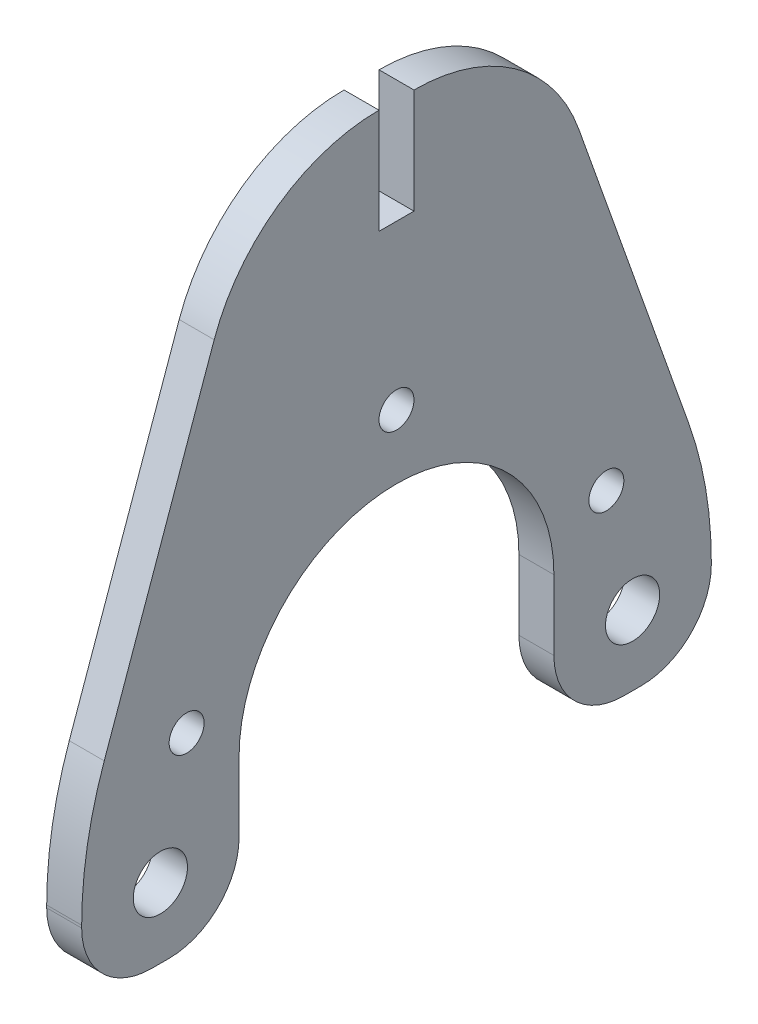
SolidWorks part; units mm, degrees
material "6061 Alloy"
ref_plane "Front Plane" through (0, 0, 0) normal (0, 0, 1) x (1, 0, 0)
ref_plane "Top Plane" through (0, 0, 0) normal (0, 1, 0) x (1, 0, 0)
ref_plane "Right Plane" through (0, 0, 0) normal (1, 0, 0) x (0, 0, -1)
sketch "Sketch1" plane through (0, 0, 0) normal (1, 0, 0) x (0, 0, -1)
  line L0 (1.5875, 44.45) -> (1.5875, 34.925)
  line L1 (1.5875, 34.925) -> (-1.5875, 34.925)
  line L2 (0, 0) -> (0, 73.524) construction
  line L3 (-1.5875, 44.45) -> (-1.5875, 34.925)
  line L4 (21.4312, -6.35) -> (-21.4312, -6.35) construction
  line L5 (16.5481, 33.885) -> (28.575, 0)
  line L6 (-16.5481, 33.885) -> (-28.575, 0)
  line L7 (28.575, 0) -> (28.575, -12.7)
  line L8 (28.575, -12.7) -> (14.2875, -12.7)
  line L9 (14.2875, -12.7) -> (14.2875, 0)
  line L10 (-14.2875, 0) -> (-14.2875, -12.7)
  line L11 (-14.2875, -12.7) -> (-28.575, -12.7)
  line L12 (-28.575, -12.7) -> (-28.575, 0)
  arc A0 (14.2875, 0) -> (-14.2875, 0) centre (0, 0) ccw
  arc A5 (16.5481, 33.885) -> (1.5875, 44.45) centre (1.5875, 28.575) ccw
  arc A10 (-16.5481, 33.885) -> (-1.5875, 44.45) centre (-1.5875, 28.575) cw
  circle A11 centre (21.4312, -6.35) radius 2.5797 construction
  circle A12 centre (-21.4312, -6.35) radius 2.5797 construction
  point P1 (0, -6.35)
  point P9 (21.4312, -12.7)
  point P18 (0, 34.925)
  dimension "D1" = 28.575
  dimension "D3" = 57.15
  dimension "D4" = 15.875
  dimension "D5" = 12.7
  dimension "D6" = 42.8625
  dimension "D7" = 14.2875
  dimension "D9" = 5.1594
  dimension "D2" = 3.175
  dimension "D10" = 6.35
  dimension "D12" = 9.525
extrude "Boss-Extrude1" add sketch "Sketch1" along normal blind 3.175
hole_wizard "#10 (0.1935) Diameter Hole1" positions "Sketch2" profile "Sketch3" hole size "#10" standard "ANSI Inch"
sketch "Sketch2" plane through (0, 0, 0) normal (-1, 0, 0) x (0, 0, 1)
  line L2 (-21.4312, -6.35) -> (21.4312, -6.35) construction
  point P0 (-21.4312, -6.35)
  point P2 (21.4312, -6.35)
  point P29 (0, -6.35)
  dimension "D1" = 42.8625
  dimension "D2" = 6.35
sketch "Sketch3" plane through (0, -6.35, -21.4312) normal (0, 1, 0) x (0, 0, 1)
  line L0 (0, 0) -> (0, 20.4786)
  line L1 (0, 20.4786) -> (2.4574, 19.002)
  line L2 (2.4574, 19.002) -> (2.4574, 0)
  line L5 (2.4574, 0) -> (0, 0)
  line L10 (0, 20.4786) -> (-2.4574, 19.002) construction
  line L11 (0, -6.35) -> (0, 107.95) construction
  dimension "Hole Dia." = 4.9149
  dimension "Hole Depth" = 19.002
  dimension "Drill Angle" = 118
sketch "Sketch4" plane through (3.175, 0, 0) normal (1, 0, 0) x (0, 0, -1)
  circle A6 centre (0, 20.0978) radius 1.5875 construction
  circle A7 centre (0, 20.0978) radius 1.5875
  circle A8 centre (-19.0489, 4.2227) radius 1.5875 construction
  circle A9 centre (-19.0489, 4.2227) radius 1.5875
  circle A10 centre (19.0489, 4.2228) radius 1.5875 construction
  circle A11 centre (19.0489, 4.2228) radius 1.5875
extrude "Cut-Extrude1" cut sketch "Sketch4" against normal through all
fillet "Fillet2" radius 35.56 2 edges at (1.5875, 0, 28.575) (1.5875, 0, -28.575)
fillet "Fillet1" radius 6.35 4 edges at (1.5875, -12.7, -28.575) (1.5875, -12.7, -14.2875) (1.5875, -12.7, 28.575) (1.5875, -12.7, 14.2875)
sketch "Sketch5" [suppressed] plane through (3.175, 0, 0) normal (1, 0, 0) x (0, 0, -1)
  line L0 (-16.5481, 33.885) -> (-26.5267, 5.7708) construction
  line L1 (-4.7625, 44.1293) -> (-25.9843, 44.1293)
  line L2 (-25.9843, 44.1293) -> (-25.9843, 7.2993)
  line L3 (-1.5875, 34.925) -> (-1.5875, 44.45) construction
  line L4 (-4.7625, 44.1293) -> (-4.7625, 41.2634)
  line L5 (-1.5875, 34.925) -> (-1.5875, 44.45) construction
  arc A1 (-1.5875, 44.45) -> (-16.5481, 33.885) centre (-1.5875, 28.575) ccw construction
  arc A3 (-11.1125, 27.0644) -> (-25.9843, 7.2993) centre (31.2208, -20.2657) ccw
  arc A4 (-4.7625, 41.2634) -> (-11.1125, 27.0644) centre (-23.8125, 41.2634) cw
  dimension "D1" = 3.175
  dimension "D2" = 19.05
  dimension "D4" = 63.5
  dimension "D3" = 9.525
  dimension "D5" = 36.83
extrude "Cut-Extrude2" [suppressed] cut sketch "Sketch5" against normal through all
